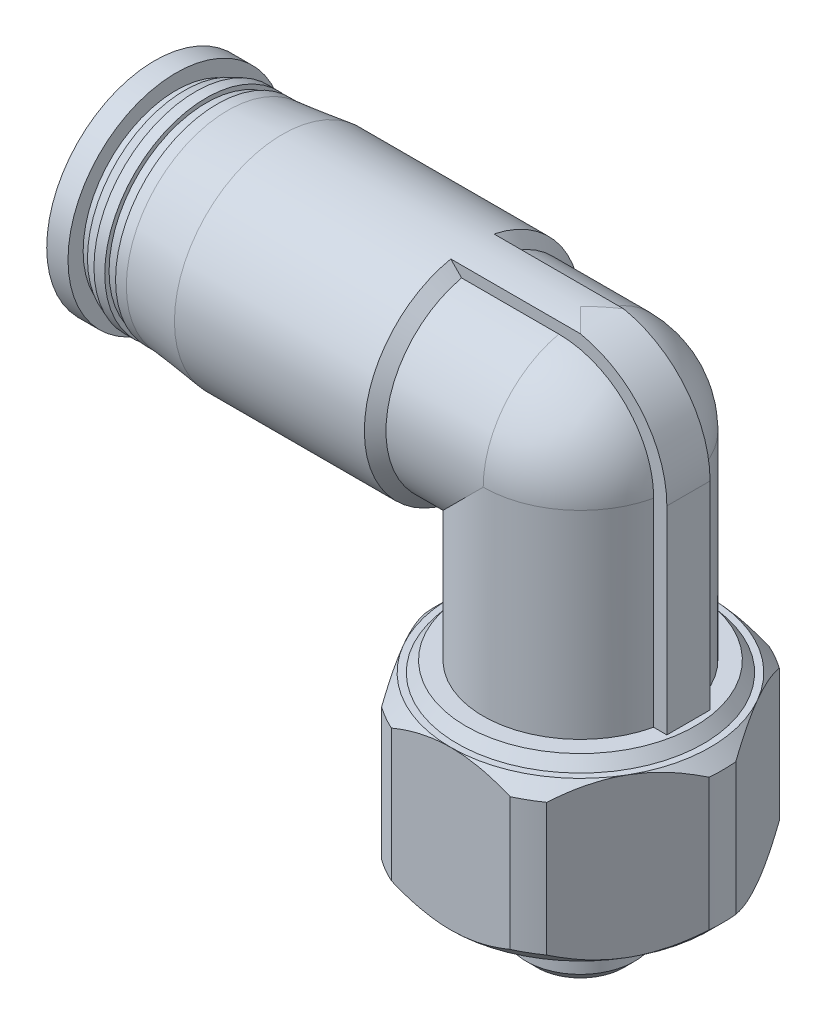
SolidWorks part; units mm, degrees
material "Free-Cutting Brass, UNS C36000"
ref_plane "Front Plane" through (0, 0, 0) normal (0, 0, 1) x (1, 0, 0)
ref_plane "Top Plane" through (0, 0, 0) normal (0, 1, 0) x (1, 0, 0)
ref_plane "Right Plane" through (0, 0, 0) normal (1, 0, 0) x (0, 0, -1)
ref_plane "Plane1" through (0, 0, 0) normal (0, 0, 1) x (1, 0, 0)
sketch "Sketch1" plane through (0, 0, 0) normal (0, 0, 1) x (1, 0, 0)
  line L0 (0, 0) -> (-6, 0)
  line L1 (-6, 0) -> (-6.6, 0.6)
  line L2 (-6.6, 0.6) -> (-6.6, 6.7214)
  line L3 (-6.6, 6.7214) -> (-6, 7.3214)
  line L4 (-6, 7.3214) -> (-5.7, 7.3214)
  line L5 (-5.7, 7.3214) -> (-5.3, 7.8214)
  line L6 (-5.3, 7.8214) -> (-4.5, 7.8214)
  line L7 (-4.5, 7.8214) -> (-4.5, 17)
  line L8 (-4.5, 17) -> (0, 17)
  line L9 (0, 17) -> (0, 0)
  line L10 (0, 17) -> (0, 0) construction
revolve "Revolve1" add sketch "Sketch1" angle 360 about L10
ref_plane "Plane2" through (0, 0, 0) normal (0, 0, 1) x (1, 0, 0)
sketch "Sketch2" plane through (0, 0, 0) normal (0, 0, 1) x (1, 0, 0)
  line L0 (0, -3.5) -> (-2.0095, -3.5)
  line L1 (-2.0095, -3.5) -> (-2.5, -3.0095)
  line L2 (-2.5, -3.0095) -> (-2.5, -0.5)
  line L3 (-2.5, -0.5) -> (-3.6, -0.5)
  line L4 (-3.6, -0.5) -> (-3.6, 0)
  line L5 (-3.6, 0) -> (0, 0)
  line L6 (0, 0) -> (0, -3.5)
  line L7 (0, 0) -> (0, -3.5) construction
revolve "Revolve2" add sketch "Sketch2" angle 360 about L7
cosmetic thread "Cosmetic Thread1" parameters "D1"=3, "D2"=4.019
ref_plane "Plane3" through (0, 0, 0) normal (0, 1, 0) x (1, 0, 0)
sketch "Sketch3" plane through (0, 0, 0) normal (0, 1, 0) x (1, 0, 0)
  line L0 (-12, -12) -> (12, -12)
  line L1 (12, -12) -> (12, 12)
  line L2 (12, 12) -> (-12, 12)
  line L3 (-12, 12) -> (-12, -12)
  line L4 (-6.9282, 0) -> (-3.4641, -6)
  line L5 (-3.4641, -6) -> (3.4641, -6)
  line L6 (3.4641, -6) -> (6.9282, 0)
  line L7 (6.9282, 0) -> (3.4641, 6)
  line L8 (3.4641, 6) -> (-3.4641, 6)
  line L9 (-3.4641, 6) -> (-6.9282, 0)
extrude "Cut-Extrude1" cut sketch "Sketch3" along normal blind 8.2
ref_plane "Plane4" through (0, 0, 0) normal (0, 0, 1) x (1, 0, 0)
sketch "Sketch4" plane through (0, 0, 0) normal (0, 0, 1) x (1, 0, 0)
  line L0 (-19.7, 17) -> (-19.7, 22)
  line L1 (-19.7, 22) -> (-18.715, 22)
  line L2 (-18.715, 22) -> (-18.715, 21.3)
  line L3 (-18.715, 21.3) -> (-18.315, 21.3)
  line L4 (-18.315, 21.3) -> (-18.315, 21.5)
  line L5 (-18.315, 21.5) -> (-17.815, 21.7)
  line L6 (-17.815, 21.7) -> (-17.315, 21.7)
  line L7 (-17.315, 21.7) -> (-17.315, 21.5)
  line L8 (-17.315, 21.5) -> (-16.815, 21.5)
  line L9 (-16.815, 21.5) -> (-16.815, 21.7)
  line L10 (-16.815, 21.7) -> (-16.315, 21.7)
  line L11 (-16.315, 21.7) -> (-13.79, 22)
  line L12 (-13.79, 22) -> (-5, 22)
  line L13 (-5, 22) -> (-4.5, 21.5)
  line L14 (-4.5, 21.5) -> (0, 21.5)
  line L15 (4.5, 17) -> (-19.7, 17)
  line L16 (4.5, 17) -> (-19.7, 17) construction
  arc A0 (0, 21.5) -> (4.5, 17) centre (0, 17) cw
revolve "Revolve3" add sketch "Sketch4" angle 360 about L16
ref_plane "Plane5" through (0, 0, 0) normal (0, 0, 1) x (1, 0, 0)
sketch "Sketch5" plane through (0, 0, 0) normal (0, 0, 1) x (1, 0, 0)
  line L0 (-5, 17) -> (0, 17)
  line L1 (0, 17) -> (0, 5.7)
  line L2 (0, 5.7) -> (5, 5.7)
  line L3 (5, 5.7) -> (5, 17)
  line L4 (0, 22) -> (-5, 22)
  line L5 (-5, 22) -> (-5, 17)
  arc A0 (5, 17) -> (0, 22) centre (0, 17) ccw
extrude "Boss-Extrude1" add sketch "Sketch5" against normal blind 1 and the other way blind 1
ref_plane "Plane6" through (0, 0, 0) normal (1, 0, 0) x (0, 0, -1)
sketch "Sketch6" plane through (0, 0, 0) normal (1, 0, 0) x (0, 0, -1)
  circle A0 centre (0, 17) radius 2
extrude "Cut-Extrude2" cut sketch "Sketch6" against normal blind 19.7
ref_plane "Plane7" through (0, 0, 0) normal (0, 0, 1) x (1, 0, 0)
sketch "Sketch7" plane through (0, 0, 0) normal (0, 0, 1) x (1, 0, 0)
  line L0 (0, -3.5) -> (-1.25, -3.5)
  line L1 (-1.25, -3.5) -> (-1.25, 1)
  line L2 (-1.25, 1) -> (-2, 1)
  line L3 (-2, 1) -> (-2, 17)
  line L4 (0, 19) -> (0, -3.5)
  line L5 (0, 19) -> (0, -3.5) construction
  arc A0 (-2, 17) -> (0, 19) centre (0, 17) cw
revolve "Cut-Revolve1" cut sketch "Sketch7" angle 360 about L5
ref_plane "Plane8" through (0, 0, 0) normal (0, 0, 1) x (1, 0, 0)
sketch "Sketch8" plane through (0, 0, 0) normal (0, 0, 1) x (1, 0, 0)
  line L0 (-7, 24) -> (-7, 22)
  line L1 (-7, 22) -> (3, 22)
  line L2 (3, 22) -> (3, 24)
  line L3 (3, 24) -> (-7, 24)
  line L4 (3, 17) -> (-7, 17) construction
revolve "Cut-Revolve2" cut sketch "Sketch8" angle 30 about L4 other way angle 30
